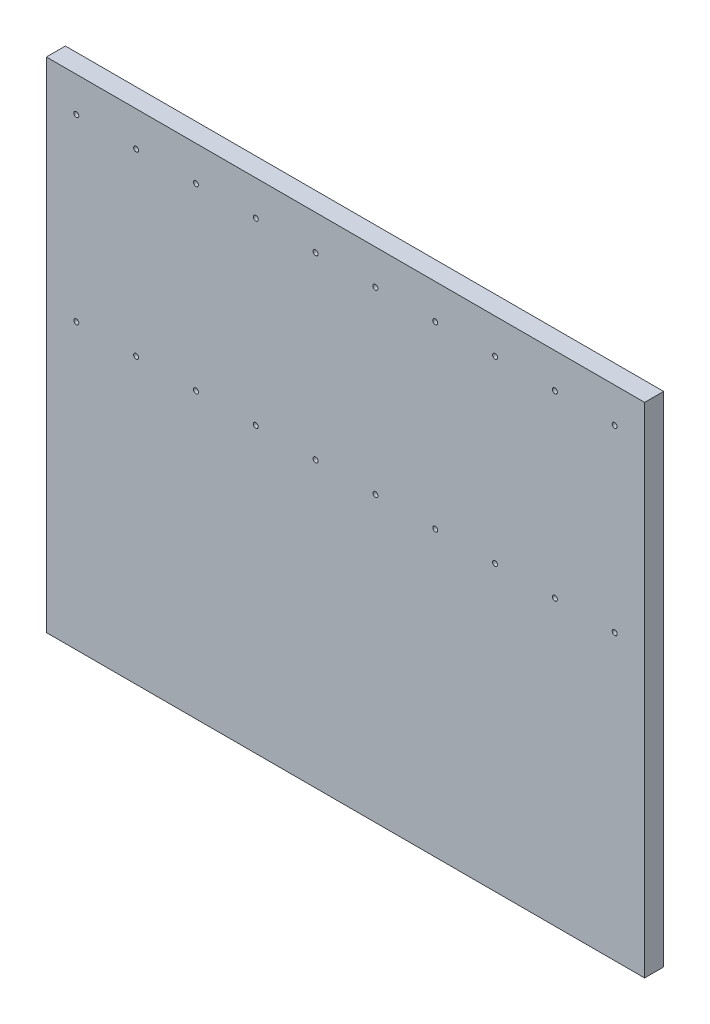
SolidWorks part; units mm, degrees
ref_plane "Front Plane" through (0, 0, 0) normal (0, 0, 1) x (1, 0, 0)
ref_plane "Top Plane" through (0, 0, 0) normal (0, 1, 0) x (1, 0, 0)
ref_plane "Right Plane" through (0, 0, 0) normal (1, 0, 0) x (0, 0, -1)
sketch "Sketch1" plane through (0, 0, 0) normal (0, 0, 1) x (1, 0, 0)
  line L0 (300, 250) -> (300, 185) construction
  line L1 (300, 250) -> (-300, 250) construction
  line L2 (300, 250) -> (300, 185)
  line L3 (300, 250) -> (-300, 250)
  line L5 (-300, -250) -> (300, -250)
  line L6 (-300, -250) -> (-300, 250)
  line L7 (-300, 250) -> (300, 250)
  line L8 (300, -250) -> (300, 250)
  dimension "D1" = 500
  dimension "D2" = 600
extrude "Boss-Extrude1" add sketch "Sketch1" along normal blind 19.05 contours L5 L8 L2 L3 L6
sketch "Sketch2" plane through (0, 0, 19.05) normal (0, 0, 1) x (1, 0, 0)
  circle A0 centre (270, 35) radius 2.5 construction
  circle A1 centre (210, 35) radius 2.5 construction
  circle A2 centre (150, 35) radius 2.5 construction
  circle A3 centre (90, 35) radius 2.5 construction
  circle A4 centre (30, 35) radius 2.5 construction
  circle A5 centre (-30, 35) radius 2.5 construction
  circle A6 centre (-90, 35) radius 2.5 construction
  circle A7 centre (-150, 35) radius 2.5 construction
  circle A8 centre (-210, 35) radius 2.5 construction
  circle A9 centre (-270, 35) radius 2.5 construction
  circle A10 centre (-270, 215) radius 2.5 construction
  circle A11 centre (-210, 215) radius 2.5 construction
  circle A12 centre (-150, 215) radius 2.5 construction
  circle A13 centre (-90, 215) radius 2.5 construction
  circle A14 centre (-30, 215) radius 2.5 construction
  circle A15 centre (30, 215) radius 2.5 construction
  circle A16 centre (90, 215) radius 2.5 construction
  circle A17 centre (150, 215) radius 2.5 construction
  circle A18 centre (210, 215) radius 2.5 construction
  circle A19 centre (270, 215) radius 2.5 construction
  circle A20 centre (270, 35) radius 2.5
  circle A21 centre (210, 35) radius 2.5
  circle A22 centre (150, 35) radius 2.5
  circle A23 centre (90, 35) radius 2.5
  circle A24 centre (30, 35) radius 2.5
  circle A25 centre (-30, 35) radius 2.5
  circle A26 centre (-90, 35) radius 2.5
  circle A27 centre (-150, 35) radius 2.5
  circle A28 centre (-210, 35) radius 2.5
  circle A29 centre (-270, 35) radius 2.5
  circle A30 centre (-270, 215) radius 2.5
  circle A31 centre (-210, 215) radius 2.5
  circle A32 centre (-150, 215) radius 2.5
  circle A33 centre (-90, 215) radius 2.5
  circle A34 centre (-30, 215) radius 2.5
  circle A35 centre (30, 215) radius 2.5
  circle A36 centre (90, 215) radius 2.5
  circle A37 centre (150, 215) radius 2.5
  circle A38 centre (210, 215) radius 2.5
  circle A39 centre (270, 215) radius 2.5
extrude "Cut-Extrude1" cut sketch "Sketch2" against normal blind 5
